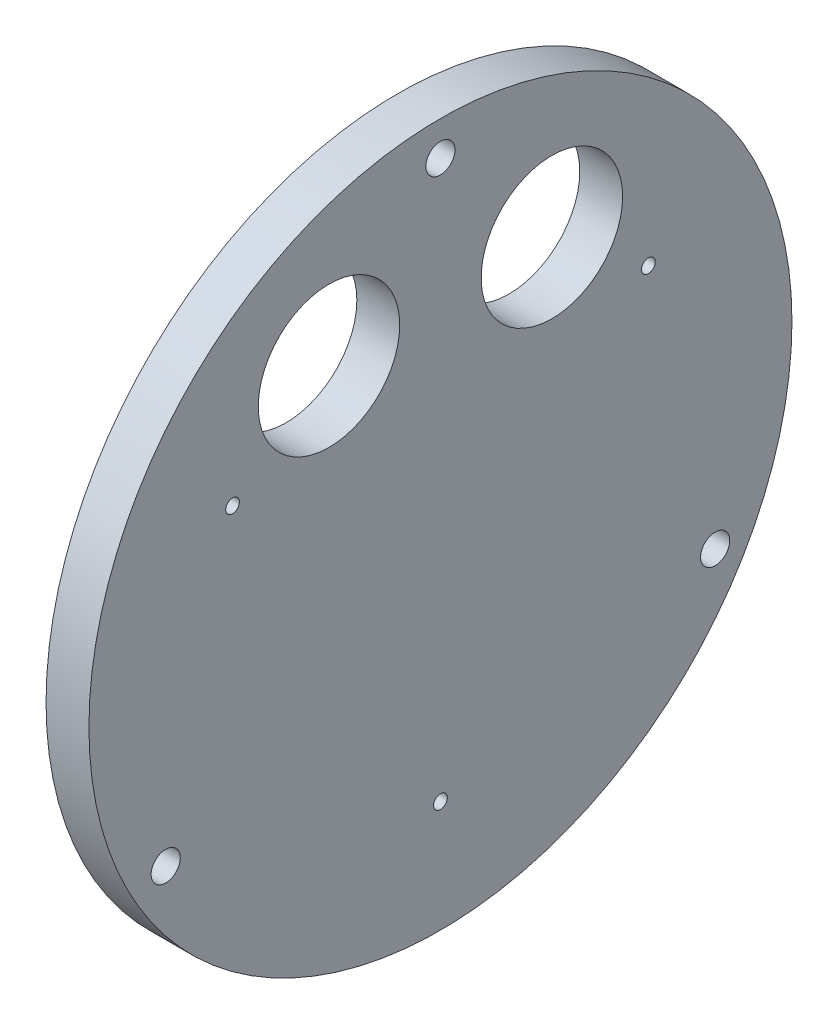
SolidWorks part; units mm, degrees
ref_plane "Front Plane" through (0, 0, 0) normal (0, 0, 1) x (1, 0, 0)
ref_plane "Top Plane" through (0, 0, 0) normal (0, 1, 0) x (1, 0, 0)
ref_plane "Right Plane" through (0, 0, 0) normal (1, 0, 0) x (0, 0, -1)
sketch "Axial blank profile" plane through (0, 0, 0) normal (0, 0, 1) x (1, 0, 0)
  line L0 (-60, 0) -> (30, 0) construction
  line L1 (-22, 0) -> (-17, 0)
  line L2 (-17, 0) -> (-17, 41)
  line L3 (-17, 41) -> (-22, 41)
  line L4 (-22, 41) -> (-22, 0)
revolve "Native revolved blank" add sketch "Axial blank profile" angle 360 about L0
sketch "Two fitting-route clearance bores diameter16p5 sketch" plane through (0, 0, 0) normal (1, 0, 0) x (0, 0, -1)
  circle A0 centre (-13, 22.5167) radius 8.25
  circle A1 centre (13, 22.5167) radius 8.25
extrude "Two fitting-route clearance bores diameter16p5" cut sketch "Two fitting-route clearance bores diameter16p5 sketch" along normal blind 5 from offset 22
sketch "Three long mounting screw clearances sketch" plane through (0, 0, 0) normal (1, 0, 0) x (0, 0, -1)
  circle A0 centre (0, 37) radius 1.7
  circle A1 centre (-32.0429, -18.5) radius 1.7
  circle A2 centre (32.0429, -18.5) radius 1.7
extrude "Three long mounting screw clearances" cut sketch "Three long mounting screw clearances sketch" along normal blind 5 from offset 22
sketch "Three M2 locator receiving pilots depth3 sketch" plane through (0, 0, 0) normal (1, 0, 0) x (0, 0, -1)
  circle A0 centre (-24.2487, 14) radius 0.8
  circle A1 centre (0, -28) radius 0.8
  circle A2 centre (24.2487, 14) radius 0.8
extrude "Three M2 locator receiving pilots depth3" cut sketch "Three M2 locator receiving pilots depth3 sketch" along normal blind 3 from offset 20
